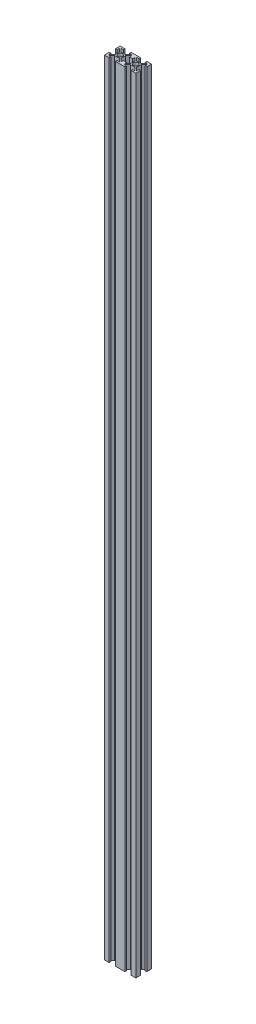
SolidWorks part; units mm, degrees
material "1060 Alloy"
ref_plane "Front Plane" through (0, 0, 0) normal (0, 0, 1) x (1, 0, 0)
ref_plane "Top Plane" through (0, 0, 0) normal (0, 1, 0) x (1, 0, 0)
ref_plane "Right Plane" through (0, 0, 0) normal (1, 0, 0) x (0, 0, -1)
sketch "2020 sketch" plane through (0, 0, 0) normal (0, 1, 0) x (1, 0, 0)
  line L0 (-4, 10) -> (-4, 8)
  line L1 (-10, 10) -> (-4, 10)
  line L2 (-10, 10) -> (-10, 4)
  line L3 (-10, -10) -> (-4, -10)
  line L4 (10, 10) -> (10, 4)
  line L5 (-10, 10) -> (10, -10) construction
  line L6 (-10, -10) -> (10, 10) construction
  line L7 (-4, 8) -> (-7, 8)
  line L8 (-7, 8) -> (-3, 4)
  line L9 (-3, 4) -> (3, 4)
  line L10 (3, 4) -> (7, 8)
  line L11 (7, 8) -> (4, 8)
  line L12 (4, 8) -> (4, 10)
  line L13 (4, 3) -> (4, -3)
  line L14 (8, 7) -> (4, 3)
  line L15 (8, 4) -> (8, 7)
  line L16 (10, 4) -> (8, 4)
  line L17 (8, -4) -> (10, -4)
  line L18 (8, -7) -> (8, -4)
  line L19 (4, -3) -> (8, -7)
  line L20 (3, -4) -> (-3, -4)
  line L21 (7, -8) -> (3, -4)
  line L22 (4, -8) -> (7, -8)
  line L23 (4, -10) -> (4, -8)
  line L24 (-4, -8) -> (-4, -10)
  line L25 (-7, -8) -> (-4, -8)
  line L26 (-3, -4) -> (-7, -8)
  line L27 (-4, -3) -> (-4, 3)
  line L28 (-8, -7) -> (-4, -3)
  line L29 (-8, -4) -> (-8, -7)
  line L30 (-10, -4) -> (-8, -4)
  line L31 (-8, 4) -> (-10, 4)
  line L32 (-8, 7) -> (-8, 4)
  line L33 (-4, 3) -> (-8, 7)
  line L34 (-10, -4) -> (-10, -10)
  line L35 (10, -4) -> (10, -10)
  line L36 (4, 10) -> (10, 10)
  line L37 (4, -10) -> (10, -10)
  circle A0 centre (0, 0) radius 3
  point P0 (0, 0)
  point P14 (4, 9)
  point P42 (0, 0)
  dimension "D9" = 6
  dimension "D1" = 20
  dimension "D2" = 20
  dimension "D3" = 8
  dimension "D4" = 6
  dimension "D5" = 6
  dimension "D6" = 2
  dimension "D7" = 4
  dimension "D8" = 4
extrude "Boss-Extrude1" add sketch "2020 sketch" along normal blind 1000 contours A0 | L28 L27 L33 L32 L31 L2 L1 L0 L7 L8 L9 L10 L11 L12 L36 L4 L16 L15 L14 L13 L19 L18 L17 L35 L37 L23 L22 L21 L20 L26 L25 L24 L3 L34 L30 L29
mirror "Mirror1" about plane through (10, 1000, 4) normal (1, 0, 0) of "Boss-Extrude1"
